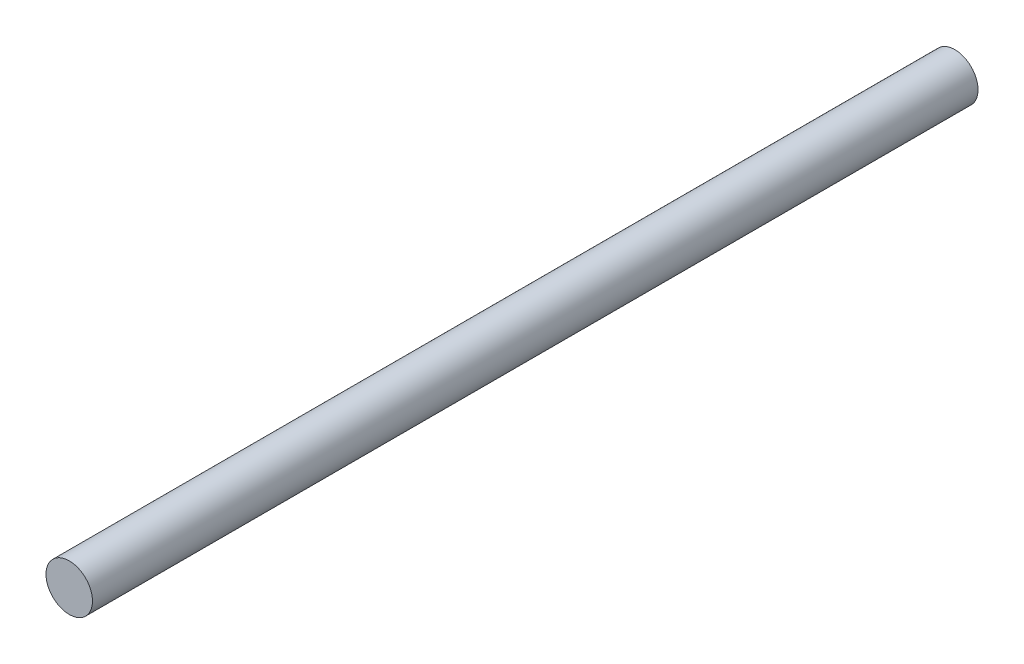
SolidWorks part; units mm, degrees
ref_plane "Front Plane" through (0, 0, 0) normal (0, 0, 1) x (1, 0, 0)
ref_plane "Top Plane" through (0, 0, 0) normal (0, 1, 0) x (1, 0, 0)
ref_plane "Right Plane" through (0, 0, 0) normal (1, 0, 0) x (0, 0, -1)
sketch "Sketch1" plane through (0, 0, 0) normal (0, 0, 1) x (1, 0, 0)
  circle A0 centre (0, 0) radius 2
  dimension "D1" = 4
extrude "Boss-Extrude1" add sketch "Sketch1" along normal blind 76.2
